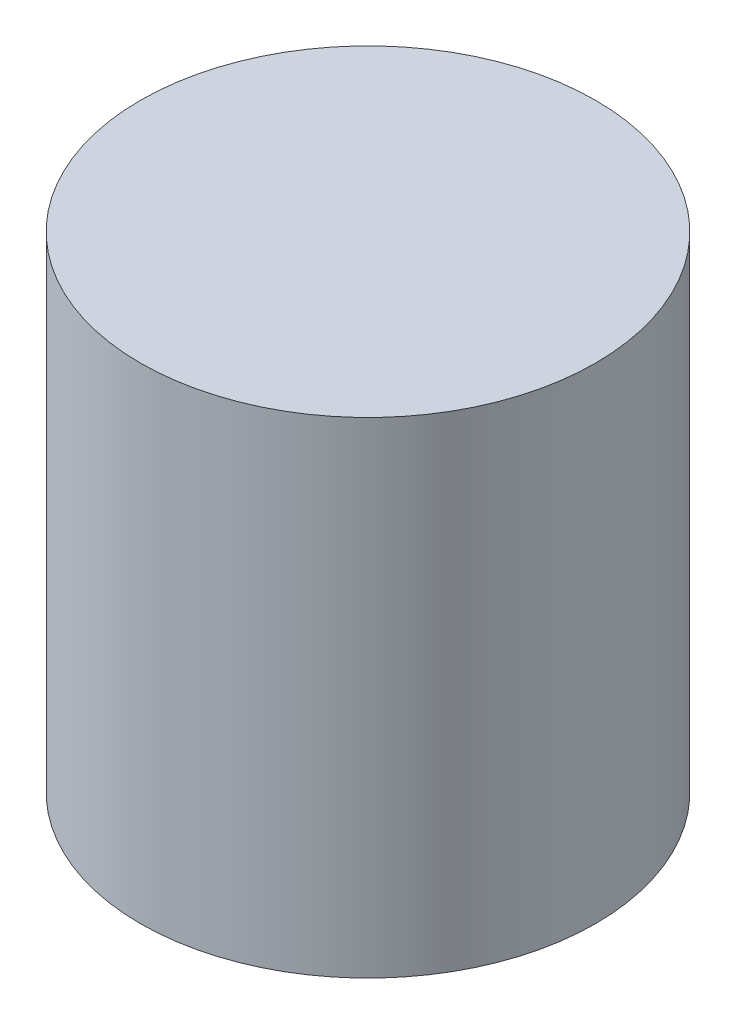
SolidWorks part; units mm, degrees
ref_plane "Plan de face" through (0, 0, 0) normal (0, 0, 1) x (1, 0, 0)
ref_plane "Plan de dessus" through (0, 0, 0) normal (0, 1, 0) x (1, 0, 0)
ref_plane "Plan de droite" through (0, 0, 0) normal (1, 0, 0) x (0, 0, -1)
sketch "Esquisse1" plane through (0, 0, 0) normal (0, 1, 0) x (1, 0, 0)
  circle A0 centre (0, 0) radius 37.5
  dimension "D1" = 75
extrude "Boss.-Extru.1" add sketch "Esquisse1" along normal blind 80
sketch "Esquisse2" plane through (0, 0, 0) normal (0, -1, 0) x (1, 0, 0)
  circle A0 centre (0, 0) radius 4
  dimension "D1" = 8
extrude "Enlèv. mat.-Extru.1" cut sketch "Esquisse2" against normal blind 13.7
